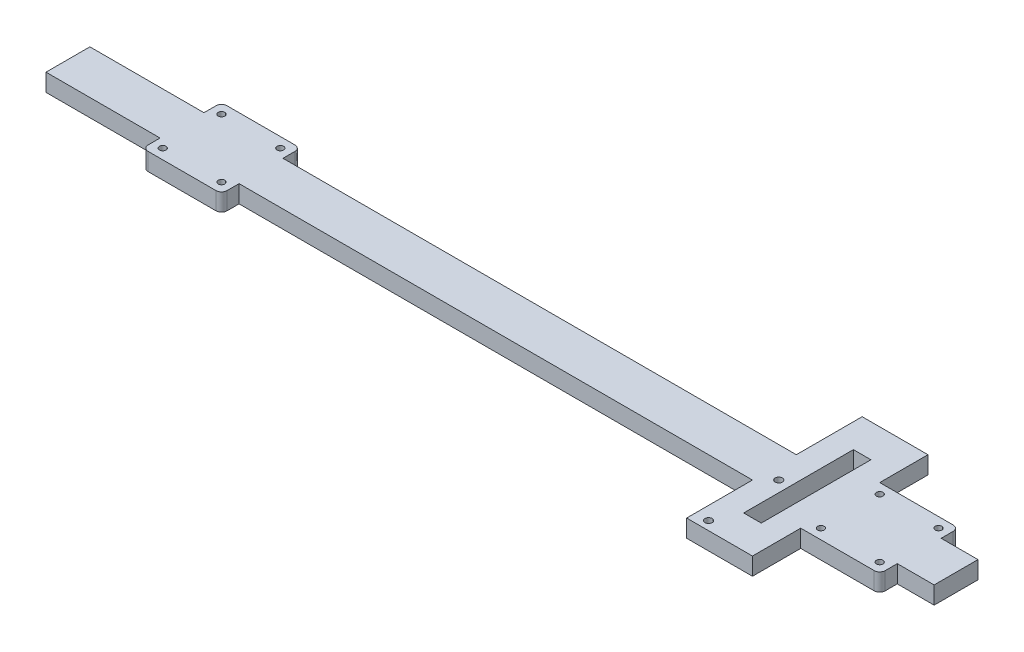
SolidWorks part; units mm, degrees
ref_plane "Front" through (0, 0, 0) normal (0, 0, 1) x (1, 0, 0)
ref_plane "Top" through (0, 0, 0) normal (0, 1, 0) x (1, 0, 0)
ref_plane "Right" through (0, 0, 0) normal (1, 0, 0) x (0, 0, -1)
sketch "Sketch1" plane through (0, 0, 0) normal (0, 1, 0) x (1, 0, 0)
  line L1 (0, 0) -> (264.8, 0) construction
  line L2 (0, 0) -> (0, -156.4) construction
  line L3 (0, -156.4) -> (264.8, -156.4) construction
  line L4 (264.8, 0) -> (264.8, -156.4) construction
  line L5 (0, -68.2) -> (264.8, -68.2)
  line L6 (0, -68.2) -> (0, -88.2)
  line L7 (0, -88.2) -> (264.8, -88.2)
  line L8 (264.8, -68.2) -> (264.8, -88.2)
  line L9 (0, -68.2) -> (-70, -68.2)
  line L10 (0, -68.2) -> (0, -88.2)
  line L11 (0, -88.2) -> (-70, -88.2)
  line L12 (-70, -68.2) -> (-70, -88.2)
  line L13 (264.8, -68.2) -> (334.8, -68.2)
  line L14 (264.8, -68.2) -> (264.8, -88.2)
  line L15 (264.8, -88.2) -> (334.8, -88.2)
  line L16 (334.8, -68.2) -> (334.8, -88.2)
  dimension "D1" = 264.8
  dimension "D2" = 156.4
  dimension "D3" = 20
  dimension "D4" = 68.2
  dimension "D5" = 70
  dimension "D6" = 70
extrude "大梁" add sketch "Sketch1" along normal blind 8 contours L9 L12 L11 L6 | L8 L5 L6 L7 | L16 L13 L8 L15
sketch "Sketch2" plane through (0, 0, 68.2) normal (0, 0, -1) x (-1, 0, 0)
  line L0 (-334.8, 8) -> (70, 8) construction
  line L1 (18, 8) -> (-18, 8)
  line L2 (18, 8) -> (18, 0)
  line L3 (18, 0) -> (-18, 0)
  line L4 (-18, 8) -> (-18, 0)
  line L5 (-334.8, 0) -> (70, 0) construction
  line L6 (70, 8) -> (70, 0) construction
  line L7 (-282, 0) -> (-318, 0)
  line L8 (-318, 8) -> (-318, 0)
  line L9 (-282, 8) -> (-318, 8)
  line L10 (-282, 8) -> (-282, 0)
  dimension "D1" = 36
  dimension "D2" = 52
  dimension "D3" = 2
extrude "Boss-Extrude2" add sketch "Sketch2" along normal blind 8
sketch "Sketch4" plane through (0, 0, 88.2) normal (0, 0, 1) x (1, 0, 0)
  line L0 (334.8, 0) -> (-70, 0) construction
  line L1 (18, 0) -> (-18, 0)
  line L2 (18, 0) -> (18, 8)
  line L3 (18, 8) -> (-18, 8)
  line L4 (-18, 0) -> (-18, 8)
  line L5 (334.8, 8) -> (-70, 8) construction
  line L7 (-70, 8) -> (-70, 0) construction
  line L8 (318, 0) -> (282, 0)
  line L9 (318, 8) -> (282, 8)
  line L10 (318, 0) -> (318, 8)
  line L11 (282, 0) -> (282, 8)
  dimension "D1" = 36
  dimension "D2" = 52
  dimension "D3" = 2
extrude "Boss-Extrude3" add sketch "Sketch4" along normal blind 8
sketch "Sketch5" plane through (0, 8, 0) normal (0, 1, 0) x (1, 0, 0)
  line L0 (-18, -96.2) -> (-18, -88.2) construction
  line L1 (18, -96.2) -> (-18, -96.2) construction
  circle A0 centre (-13.4, -91.6) radius 1.5
  circle A1 centre (13.4, -91.6) radius 1.5
  circle A2 centre (13.4, -64.8) radius 1.5
  circle A3 centre (-13.4, -64.8) radius 1.5
  circle A4 centre (313.4, -91.6) radius 1.5
  circle A5 centre (286.6, -64.8) radius 1.5
  circle A6 centre (313.4, -64.8) radius 1.5
  circle A7 centre (286.6, -91.6) radius 1.5
  dimension "D1" = 3
  dimension "D2" = 4.6
  dimension "D3" = 4.6
  dimension "D4" = 2
  dimension "D5" = 2
  dimension "D6" = 2
extrude "Cut-Extrude1" cut sketch "Sketch5" against normal through all
fillet "Fillet1" radius 2.5 6 edges at (318, 4, 60.2) (318, 4, 96.2) (-18, 4, 96.2) (18, 4, 96.2) (-18, 4, 60.2) (18, 4, 60.2)
sketch "Sketch6" plane through (0, 0, 88.2) normal (0, 0, 1) x (1, 0, 0)
  line L0 (282, 0) -> (18, 0) construction
  line L1 (282, 8) -> (252, 8)
  line L2 (282, 8) -> (282, 0)
  line L3 (282, 0) -> (252, 0)
  line L4 (252, 8) -> (252, 0)
  dimension "D1" = 30
extrude "Boss-Extrude4" add sketch "Sketch6" along normal blind 30
sketch "Sketch7" plane through (0, 0, 68.2) normal (0, 0, -1) x (-1, 0, 0)
  line L0 (-282, 8) -> (-18, 8) construction
  line L1 (-282, 0) -> (-252, 0)
  line L2 (-282, 0) -> (-282, 8)
  line L3 (-282, 8) -> (-252, 8)
  line L4 (-252, 0) -> (-252, 8)
  dimension "D1" = 30
extrude "Boss-Extrude5" add sketch "Sketch7" along normal blind 30
sketch "Sketch8" plane through (0, 8, 0) normal (0, 1, 0) x (1, 0, 0)
  line L0 (252, -38.2) -> (282, -38.2) construction
  line L1 (271, -53.2) -> (263, -53.2)
  line L2 (271, -53.2) -> (271, -103.2)
  line L3 (271, -103.2) -> (263, -103.2)
  line L4 (263, -53.2) -> (263, -103.2)
  line L5 (252, -118.2) -> (252, -88.2) construction
  dimension "D1" = 50
  dimension "D2" = 8
  dimension "D3" = 15
  dimension "D4" = 11
extrude "Cut-Extrude2" cut sketch "Sketch8" against normal through all
sketch "Sketch11" plane through (0, 8, 0) normal (0, 1, 0) x (1, 0, 0)
  line L0 (282, -118.2) -> (252, -118.2) construction
  line L1 (263, -53.2) -> (263, -103.2) construction
  circle A0 centre (258, -114.2) radius 1.65
  circle A1 centre (258, -82.2) radius 1.65
  dimension "D1" = 3.3
  dimension "D2" = 4
  dimension "D3" = 5
  dimension "D4" = 2
extrude "Cut-Extrude3" cut sketch "Sketch11" against normal through all
equation "\"offset\"= 0.3"
equation "\"v\"= 0.1"
equation "\"D1@Sketch11\"=\"offset\"+3"
